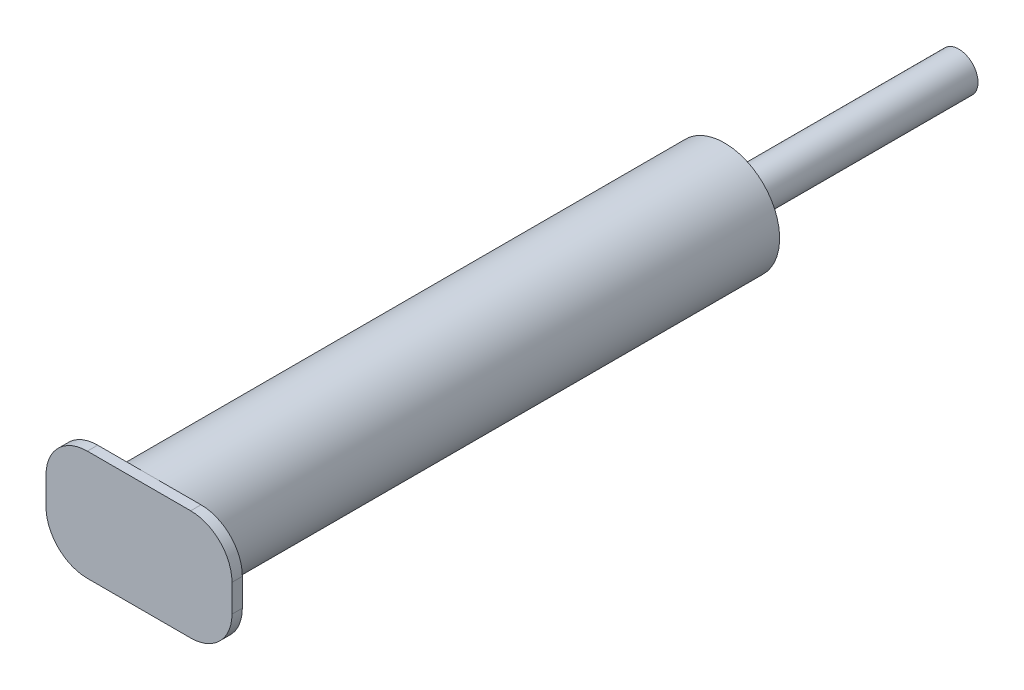
SolidWorks part; units mm, degrees
ref_plane "Front Plane" through (0, 0, 0) normal (1, 0, 0) x (0, 1, 0)
ref_plane "Top Plane" through (0, 0, 0) normal (0, 0, 1) x (0, 1, 0)
ref_plane "Right Plane" through (0, 0, 0) normal (0, 1, 0) x (-1, 0, 0)
sketch "Sketch1" plane through (0, 0, 0) normal (0, 0, 1) x (0, 1, 0)
  circle A0 centre (0, 0) radius 8
  point P2 (0, 0)
  dimension "D1" = 16
extrude "Boss-Extrude1" add sketch "Sketch1" along normal blind 85
sketch "Sketch2" plane through (0, 0, 0) normal (0, 0, -1) x (1, 0, 0)
  circle A0 centre (0, 0) radius 8
  circle A1 centre (0, 0) radius 8 construction
extrude "Boss-Extrude3" add sketch "Sketch2" along normal blind 3 draft 60
sketch "Sketch3" plane through (0, 0, -3) normal (0, 0, -1) x (1, 0, 0)
  circle A0 centre (0, 0) radius 2.8038
  circle A1 centre (0, 0) radius 2.8038 construction
extrude "Boss-Extrude4" add sketch "Sketch3" along normal blind 31
sketch "Sketch4" plane through (0, 0, 85) normal (0, 0, 1) x (1, 0, 0)
  line L5 (-7.5, 8) -> (7.5, 8)
  line L6 (-13.5, 2) -> (-13.5, -2)
  line L7 (-7.5, -8) -> (7.5, -8)
  line L8 (13.5, 2) -> (13.5, -2)
  line L9 (-13.5, 8) -> (13.5, -8) construction
  line L10 (-13.5, -8) -> (13.5, 8) construction
  arc A0 (-13.5, -2) -> (-7.5, -8) centre (-7.5, -2) ccw
  arc A1 (7.5, -8) -> (13.5, -2) centre (7.5, -2) ccw
  arc A2 (7.5, 8) -> (13.5, 2) centre (7.5, 2) cw
  arc A3 (-7.5, 8) -> (-13.5, 2) centre (-7.5, 2) ccw
  point P0 (0, 0)
  point P5 (0, 0)
  dimension "D3" = 6
  dimension "D1" = 27
  dimension "D2" = 16
extrude "Boss-Extrude5" add sketch "Sketch4" against normal blind 1.5
